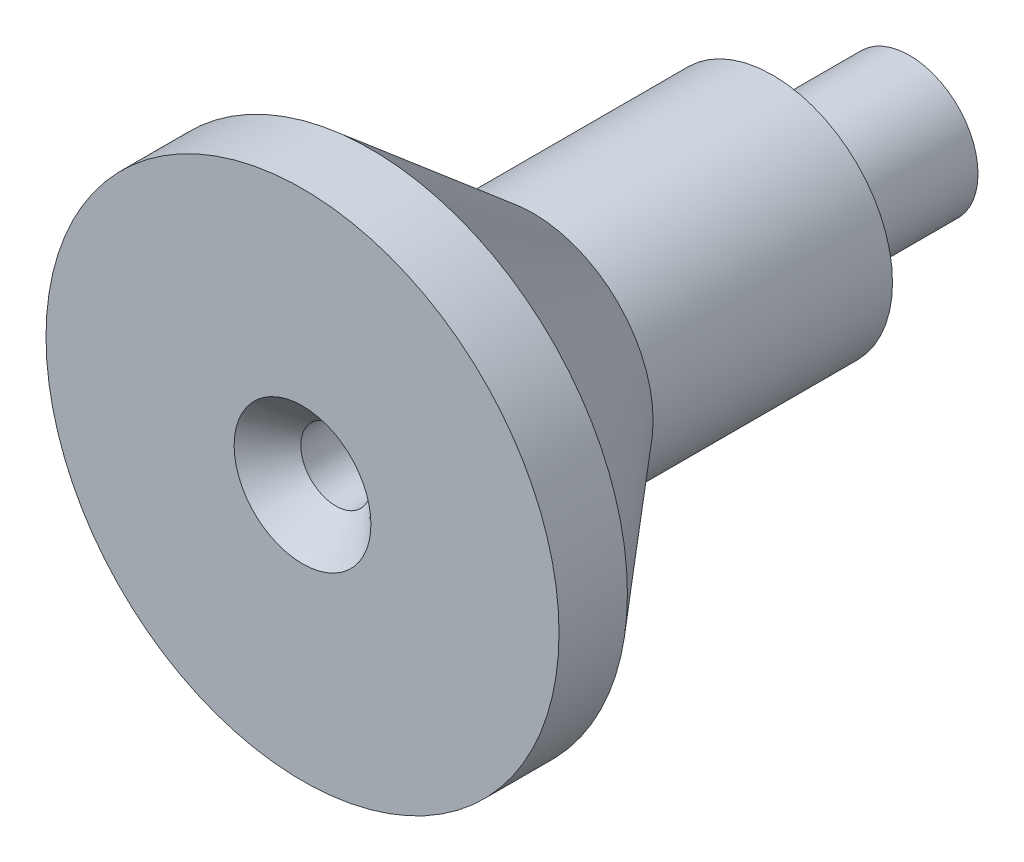
SolidWorks part; units mm, degrees
ref_plane "Plano frontal" through (0, 0, 0) normal (0, 0, 1) x (1, 0, 0)
ref_plane "Plano superior" through (0, 0, 0) normal (0, 1, 0) x (1, 0, 0)
ref_plane "Plano direito" through (0, 0, 0) normal (1, 0, 0) x (0, 0, -1)
sketch "Esboço1" plane through (0, 0, 0) normal (0, 1, 0) x (1, 0, 0)
  line L0 (0, 0) -> (7.5, 0)
  line L1 (7.5, 0) -> (7.5, 2)
  line L3 (3.5, 6.75) -> (3.5, 13.75)
  line L4 (3.5, 13.75) -> (2, 13.75)
  line L5 (2, 13.75) -> (2, 17.75)
  line L6 (2, 17.75) -> (0, 17.75)
  line L7 (0, 0) -> (0, 24.1131) construction
  line L8 (0, 0) -> (0, 17.75)
  line L10 (7.5, 2) -> (3.5, 6.75)
  dimension "D1" = 7.5
  dimension "D2" = 2
  dimension "D3" = 3.5
  dimension "D4" = 4.75
  dimension "D5" = 2
  dimension "D6" = 7
  dimension "D7" = 4
revolve "Revolução1" add sketch "Esboço1" angle 360 about L7
sketch "Esboço8" plane through (0, 0, 0) normal (0, 1, 0) x (1, 0, 0)
  line L0 (0, 0) -> (2, 0)
  line L1 (2, 0) -> (0, 2)
  line L2 (0, 3.1991) -> (0, 0) construction
  line L3 (0, 0) -> (0, 2)
  dimension "D1" = 2
  dimension "D2" = 2
revolve "Corte-Revolução3" cut sketch "Esboço8" angle 360 about L2
hole_wizard "Broca de rosquear para tarraxa de M2.5x0.451" positions "Esboço9" profile "Esboço10" hole size "M2.5x0.45" standard "Ansi Metric" end condition through all
sketch "Esboço9" plane through (0, 0, 0) normal (0, 0, 1) x (1, 0, 0)
  point P0 (0, 0)
sketch "Esboço10" plane through (0, 0, 0) normal (1, 0, 0) x (0, -1, 0)
  line L0 (0, 0) -> (0, 17.75)
  line L1 (0, 17.75) -> (1.025, 17.75)
  line L2 (1.025, 17.75) -> (1.025, 0)
  line L5 (1.025, 0) -> (0, 0)
  line L11 (0, -6.35) -> (0, 107.95) construction
  dimension "Thru Hole Dia." = 2.05
  dimension "Thru Hole Depth" = 17.75
hole_wizard "Furo roscado de M3x0.53" positions "Esboço13" profile "Esboço14" tap size "M3x0.5" standard "Ansi Metric"
sketch "Esboço13" plane through (0, 0, -17.75) normal (0, 0, -1) x (-1, 0, 0)
  point P0 (0, 0)
sketch "Esboço14" plane through (0, 0, -17.75) normal (1, 0, 0) x (0, 1, 0)
  line L0 (0, 0) -> (0, 10.7511)
  line L1 (0, 10.7511) -> (1.25, 10)
  line L2 (1.25, 10) -> (1.25, 0)
  line L5 (1.25, 0) -> (0, 0)
  line L10 (0, 10.7511) -> (-1.25, 10) construction
  line L11 (0, -6.35) -> (0, 107.95) construction
  dimension "Tap Drill Dia." = 2.5
  dimension "Tap Drill Depth" = 10
  dimension "Drill Angle" = 118
cosmetic thread "Rosca de furo1" parameters "D1"=6, "D2"=3
